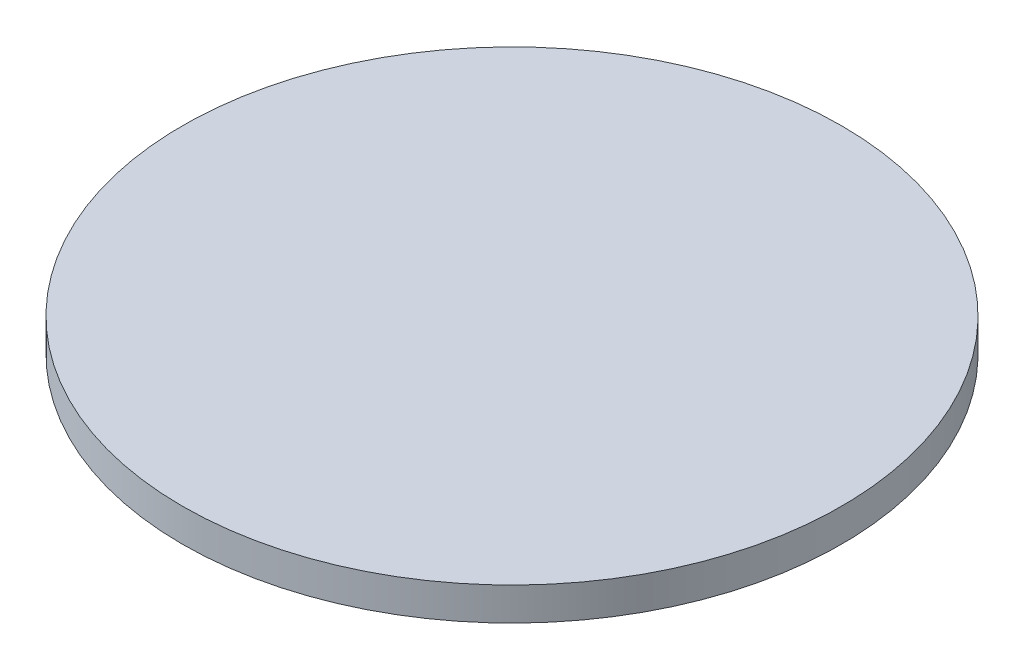
SolidWorks part; units mm, degrees
ref_plane "前视基准面" through (0, 0, 0) normal (0, 0, 1) x (1, 0, 0)
ref_plane "上视基准面" through (0, 0, 0) normal (0, 1, 0) x (1, 0, 0)
ref_plane "右视基准面" through (0, 0, 0) normal (1, 0, 0) x (0, 0, -1)
sketch "草图1" plane through (0, 0, 0) normal (0, 1, 0) x (1, 0, 0)
  circle A0 centre (0, 0) radius 50
  dimension "D1" = 100
extrude "凸台-拉伸1" add sketch "草图1" along normal blind 5
